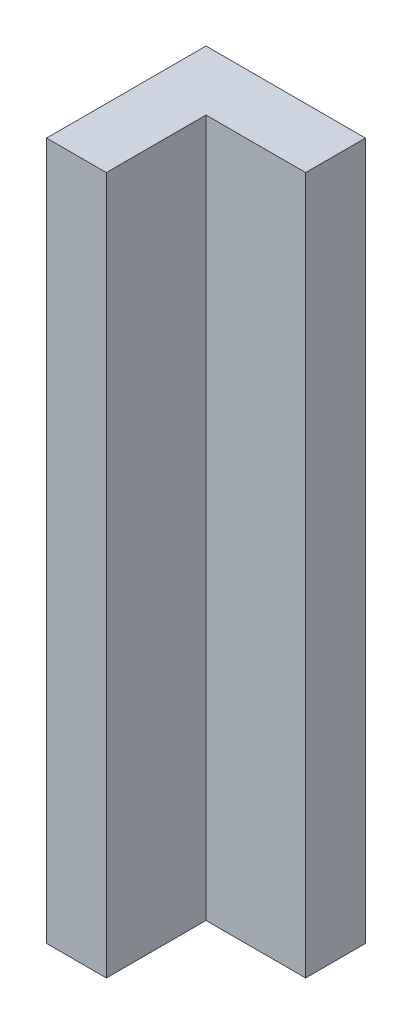
SolidWorks part; units mm, degrees
ref_plane "Front Plane" through (0, 0, 0) normal (0, 0, 1) x (1, 0, 0)
ref_plane "Top Plane" through (0, 0, 0) normal (0, 1, 0) x (1, 0, 0)
ref_plane "Right Plane" through (0, 0, 0) normal (1, 0, 0) x (0, 0, -1)
sketch "Sketch1" plane through (0, 0, 0) normal (0, 1, 0) x (1, 0, 0)
  line L0 (-7.1134, 6.6657) -> (-7.1134, -6.1343)
  line L1 (-7.1134, -6.1343) -> (-2.3134, -6.1343)
  line L2 (-2.3134, -6.1343) -> (-2.3134, 1.8657)
  line L3 (-2.3134, 1.8657) -> (5.6866, 1.8657)
  line L4 (5.6866, 1.8657) -> (5.6866, 6.6657)
  line L5 (5.6866, 6.6657) -> (-7.1134, 6.6657)
  dimension "D1" = 4.8
  dimension "D2" = 4.8
  dimension "D3" = 8
  dimension "D4" = 8
extrude "Boss-Extrude1" add sketch "Sketch1" along normal blind 56
